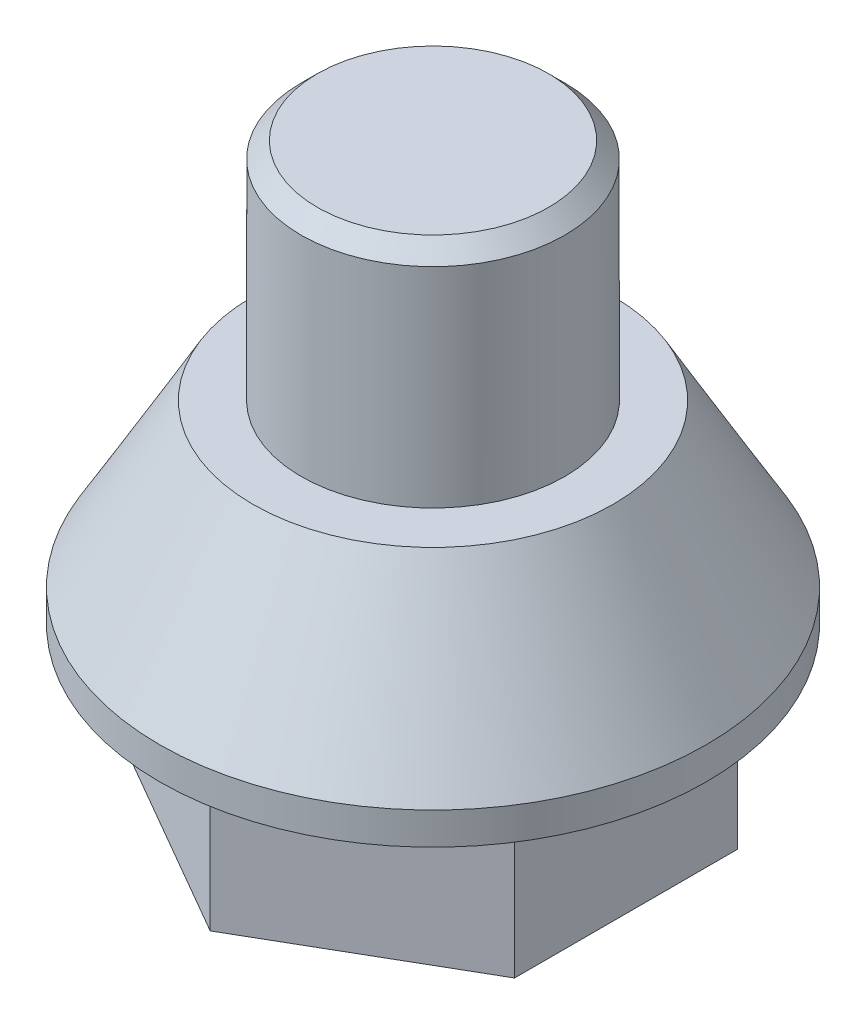
SolidWorks part; units mm, degrees
ref_plane "Front Plane" through (0, 0, 0) normal (0, 0, 1) x (1, 0, 0)
ref_plane "Top Plane" through (0, 0, 0) normal (0, 1, 0) x (1, 0, 0)
ref_plane "Right Plane" through (0, 0, 0) normal (1, 0, 0) x (0, 0, -1)
sketch "Sketch1" plane through (0, 0, 0) normal (0, 1, 0) x (1, 0, 0)
  line L0 (0, 6.9282) -> (0, -6.9282) construction
  line L1 (-6, -3.4641) -> (6, 3.4641) construction
  line L2 (6, -3.4641) -> (-6, 3.4641) construction
  line L3 (0, 6.9282) -> (6, 3.4641)
  line L4 (6, 3.4641) -> (6, -3.4641)
  line L5 (6, -3.4641) -> (0, -6.9282)
  line L6 (0, -6.9282) -> (-6, -3.4641)
  line L7 (-6, -3.4641) -> (-6, 3.4641)
  line L8 (-6, 3.4641) -> (0, 6.9282)
  dimension "D1" = 60
  dimension "D2" = 60
  dimension "D3" = 12
extrude "Boss-Extrude1" add sketch "Sketch1" along normal blind 4.8
sketch "Sketch2" plane through (0, 4.8, 0) normal (0, 1, 0) x (1, 0, 0)
  circle A0 centre (0, 0) radius 8.5
  dimension "D1" = 17
extrude "Boss-Extrude2" add sketch "Sketch2" along normal blind 1
sketch "Sketch3" plane through (0, 0, 0) normal (0, 0, 1) x (1, 0, 0)
  line L0 (0, 5.8) -> (8.5, 5.8)
  line L1 (8.5, 5.8) -> (5.6, 10.8229)
  line L2 (5.6, 10.8229) -> (4.1, 10.8229)
  line L3 (4.1, 10.8229) -> (4.1, 17.8229)
  line L4 (4.1, 17.8229) -> (0, 17.8229)
  line L5 (0, 5.8) -> (0, 17.8229)
  line L6 (8.5, 5.8) -> (-8.5, 5.8) construction
  dimension "D1" = 4.1
  dimension "D2" = 1.5
  dimension "D3" = 7
  dimension "D4" = 60
revolve "Revolve1" add sketch "Sketch3" angle 360 about L5
chamfer "Chamfer1" distance 0.5 angle 45 1 edges at (4.1, 17.8229, 0)
